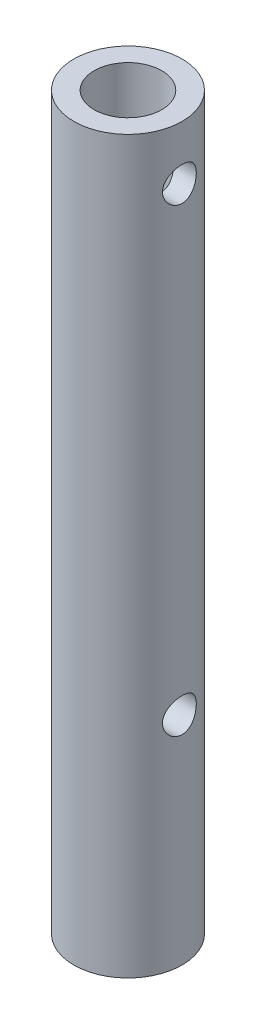
SolidWorks part; units mm, degrees
ref_plane "Front Plane" through (0, 0, 0) normal (0, 0, 1) x (1, 0, 0)
ref_plane "Top Plane" through (0, 0, 0) normal (0, 1, 0) x (1, 0, 0)
ref_plane "Right Plane" through (0, 0, 0) normal (1, 0, 0) x (0, 0, -1)
sketch "Sketch1" plane through (0, 0, 0) normal (0, 1, 0) x (1, 0, 0)
  circle A2 centre (0, 0) radius 4
  dimension "D2" = 8
extrude "Boss-Extrude1" add sketch "Sketch1" along normal blind 54
hole_wizard "Ø5.0mm Dowel Hole2" positions "3DSketch5" profile "Sketch4" hole size "Ø5.0" standard "ANSI Metric"
sketch3d "3DSketch5"
  line L0 (0, 54, 0) -> (0, 0, 0) construction
  point P0 (0, 54, 0)
sketch "Sketch4" plane through (0, 54, 0) normal (1, 0, 0) x (0, 0, 1)
  line L0 (0, 0) -> (0, 21.5022)
  line L1 (0, 21.5022) -> (2.5, 20)
  line L2 (2.5, 20) -> (2.5, 0)
  line L5 (2.5, 0) -> (0, 0)
  line L10 (0, 21.5022) -> (-2.5, 20) construction
  line L11 (0, -6.35) -> (0, 107.95) construction
  dimension "Hole Dia." = 5
  dimension "Hole Depth" = 20
  dimension "Drill Angle" = 118
hole_wizard "Tap Drill for M3x0.5 Tap2" positions "Sketch11" profile "Sketch12" hole size "M3x0.5" standard "ANSI Metric"
sketch "Sketch11" plane through (0, 0, 0) normal (1, 0, 0) x (0, 0, -1)
  line L0 (2.5, 54) -> (-2.5, 54) construction
  point P0 (0, 50)
  dimension "D1" = 4
sketch "Sketch12" plane through (0, 50, 0) normal (0, 1, 0) x (0, 0, 1)
  line L0 (0, 0) -> (0, 20.7511)
  line L1 (0, 20.7511) -> (1.25, 20)
  line L2 (1.25, 20) -> (1.25, 0)
  line L5 (1.25, 0) -> (0, 0)
  line L10 (0, 20.7511) -> (-1.25, 20) construction
  line L11 (0, -6.35) -> (0, 107.95) construction
  dimension "Hole Dia." = 2.5
  dimension "Hole Depth" = 20
  dimension "Drill Angle" = 118
hole_wizard "Tap Drill for M3x0.5 Tap3" positions "Sketch13" profile "Sketch14" hole size "M3x0.5" standard "ANSI Metric"
sketch "Sketch13" plane through (0, 0, 0) normal (1, 0, 0) x (0, 0, -1)
  line L0 (2.5, 54) -> (-2.5, 54) construction
  point P0 (0, 16)
  dimension "D1" = 38
sketch "Sketch14" plane through (0, 16, 0) normal (0, 1, 0) x (0, 0, 1)
  line L0 (0, 0) -> (0, 4)
  line L1 (0, 4) -> (1.25, 4)
  line L2 (1.25, 4) -> (1.25, 0)
  line L5 (1.25, 0) -> (0, 0)
  line L11 (0, -6.35) -> (0, 107.95) construction
  dimension "Thru Hole Dia." = 2.5
  dimension "Thru Hole Depth" = 4
hole_wizard "Tap Drill for M3x0.5 Tap4" positions "Sketch15" profile "Sketch16" hole size "M3x0.5" standard "ANSI Metric" end condition through all
sketch "Sketch15" plane through (0, 0, 0) normal (1, 0, 0) x (0, 0, -1)
  point P0 (0, 16)
sketch "Sketch16" plane through (0, 16, 0) normal (0, 1, 0) x (0, 0, -1)
  line L0 (0, 0) -> (0, 4)
  line L1 (0, 4) -> (1.25, 4)
  line L2 (1.25, 4) -> (1.25, 0)
  line L5 (1.25, 0) -> (0, 0)
  line L11 (0, -6.35) -> (0, 107.95) construction
  dimension "Thru Hole Dia." = 2.5
  dimension "Thru Hole Depth" = 4
